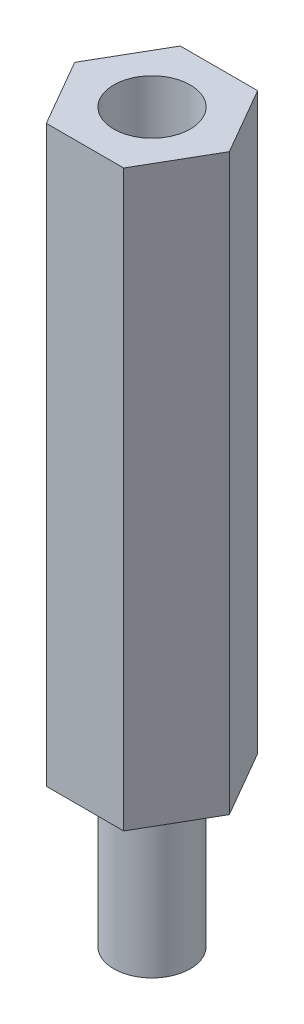
SolidWorks part; units mm, degrees
material "黄铜"
ref_plane "前视基准面" through (0, 0, 0) normal (0, 0, 1) x (1, 0, 0)
ref_plane "上视基准面" through (0, 0, 0) normal (0, 1, 0) x (1, 0, 0)
ref_plane "右视基准面" through (0, 0, 0) normal (1, 0, 0) x (0, 0, -1)
sketch "草图1" plane through (0, 0, 0) normal (0, 1, 0) x (1, 0, 0)
  line L1 (4.0415, 0) -> (2.0207, 3.5)
  line L2 (2.0207, 3.5) -> (-2.0207, 3.5)
  line L3 (-2.0207, 3.5) -> (-4.0415, 0)
  line L4 (-4.0415, 0) -> (-2.0207, -3.5)
  line L5 (-2.0207, -3.5) -> (2.0207, -3.5)
  line L6 (2.0207, -3.5) -> (4.0415, 0)
  circle A0 centre (0, 0) radius 2
  circle A1 centre (0, 0) radius 3.5 construction
  dimension "D1" = 4
  dimension "D2" = 7
extrude "凸台-拉伸1" add sketch "草图1" along normal blind 30
sketch "草图2" plane through (0, 0, 0) normal (0, -1, 0) x (1, 0, 0)
  circle A0 centre (0, 0) radius 2
  dimension "D1" = 4
extrude "凸台-拉伸2" add sketch "草图2" along normal blind 8 separate body
